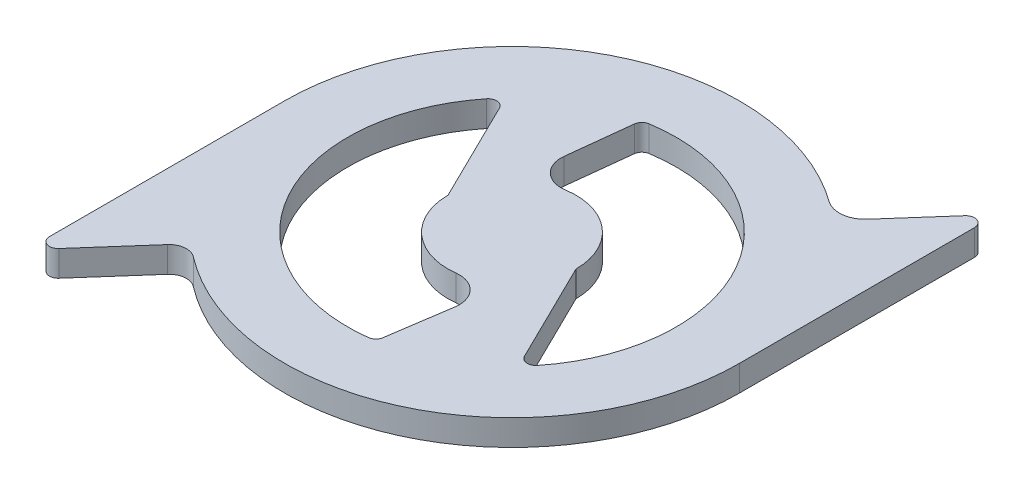
SolidWorks part; units mm, degrees
material "6061-T6 (SS)"
ref_plane "Plano frontal" through (0, 0, 0) normal (0, 0, 1) x (1, 0, 0)
ref_plane "Plano superior" through (0, 0, 0) normal (0, 1, 0) x (1, 0, 0)
ref_plane "Plano direito" through (0, 0, 0) normal (1, 0, 0) x (0, 0, -1)
sketch "Esboço1" plane through (0, 0, 0) normal (0, 1, 0) x (1, 0, 0)
  line L0 (-429.6893, 0) -> (21054.7778, 0) construction
  line L1 (0, -429.6893) -> (0, 21054.7778) construction
  line L2 (-26.4575, 0) -> (-26.4575, -30)
  line L3 (-26.4575, -30) -> (-17.5, -19.8431)
  line L4 (26.4575, 0) -> (26.4575, 30)
  line L5 (26.4575, 30) -> (17.5, 19.8431)
  line L6 (5.0097, -5.5052) -> (3.0302, -18.875)
  arc A0 (13.8948, -13.1295) -> (-3.6948, 18.7562) centre (0, 0) ccw
  arc A1 (17.5, 19.8431) -> (-26.4575, 0) centre (0, 0) ccw
  arc A2 (7.4434, 0) -> (-5.201, 5.3248) centre (0, 0) ccw
  arc A3 (-13.8948, 13.1295) -> (3.0302, -18.875) centre (0, 0) ccw
  arc A4 (-7.4434, 0) -> (5.0097, -5.5052) centre (0, 0) ccw
  arc A5 (-17.5, -19.8431) -> (26.4575, 0) centre (0, 0) ccw
  spline S0 degree 1 poles (-3.6948, 18.7562) (-5.201, 5.3248) knots 0 0 1 1
  spline S1 degree 1 poles (-13.8948, 13.1295) (-7.4434, 0) knots 0 0 1 1
  spline S2 degree 1 poles (7.4434, 0) (13.8948, -13.1295) knots 0 0 1 1
  dimension "D1" = 80
  dimension "D2" = 30
  dimension "D3" = 30
extrude "Ressalto-extrusão1" add sketch "Esboço1" along normal blind 3
fillet "Filete2" radius 1 1 edges at (26.4575, 1.5, -30)
fillet "Filete3" radius 1 1 edges at (-26.4575, 1.5, 30)
fillet "Filete4" radius 3 1 edges at (-5.201, 1.5, -5.3248)
fillet "Filete5" radius 1 1 edges at (-3.6948, 1.5, -18.7562)
fillet "Filete6" radius 2 1 edges at (-17.5, 1.5, 19.8431)
fillet "Filete8" radius 3 1 edges at (5.0097, 1.5, 5.5052)
fillet "Filete9" radius 1 1 edges at (3.0302, 1.5, 18.875)
fillet "Filete10" radius 1 1 edges at (13.8948, 1.5, 13.1295)
fillet "Filete11" radius 1 1 edges at (-13.8948, 1.5, -13.1295)
fillet "Filete12" radius 3 1 edges at (17.5, 1.5, -19.8431)
